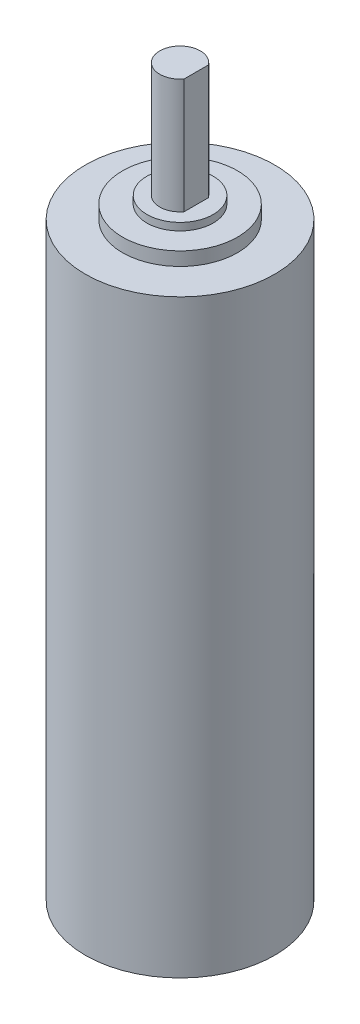
SolidWorks part; units mm, degrees
ref_plane "Спереди" through (0, 0, 0) normal (0, 0, 1) x (1, 0, 0)
ref_plane "Сверху" through (0, 0, 0) normal (0, 1, 0) x (1, 0, 0)
ref_plane "Справа" through (0, 0, 0) normal (1, 0, 0) x (0, 0, -1)
ref_plane "Плоскость1" through (0, 107.3, 0) normal (0, 1, 0) x (1, 0, 0)
ref_plane "Плоскость2" through (0, 90.3, 0) normal (0, 1, 0) x (1, 0, 0)
ref_plane "Плоскость3" through (0, 89.2, 0) normal (0, 1, 0) x (1, 0, 0)
ref_plane "Плоскость4" through (0, 87.2, 0) normal (0, 1, 0) x (1, 0, 0)
sketch "Эскиз1" plane through (0, 0, 0) normal (0, 1, 0) x (1, 0, 0)
  circle A0 centre (0, 0) radius 14
  dimension "D1" = 28
sketch "Эскиз2" plane through (0, 87.2, 0) normal (0, 1, 0) x (1, 0, 0)
  circle A0 centre (0, 0) radius 14 construction
  circle A1 centre (0, 0) radius 14
  circle A2 centre (0, 0) radius 8.5
  dimension "D1" = 17
sketch "Эскиз5" plane through (0, 89.2, 0) normal (0, 1, 0) x (1, 0, 0)
  circle A0 centre (0, 0) radius 8.5
  circle A1 centre (0, 0) radius 4.9
  dimension "D1" = 17
  dimension "D2" = 9.8
sketch "Эскиз8" plane through (0, 90.3, 0) normal (0, 1, 0) x (1, 0, 0)
  circle A0 centre (0, 0) radius 4.9
  circle A1 centre (0, 0) radius 3
  dimension "D1" = 9.8
  dimension "D2" = 6
sketch "Эскиз9" plane through (0, 107.3, 0) normal (0, 1, 0) x (1, 0, 0)
  circle A0 centre (0, 0) radius 3
  dimension "D1" = 6
loft "По сечениям2" add profiles "Эскиз1" section "Эскиз1" section "Эскиз2"
sketch "Эскиз10" plane through (0, 87.2, 0) normal (0, 1, 0) x (1, 0, 0)
  circle A0 centre (0, 0) radius 8.5 construction
  circle A1 centre (0, 0) radius 8.5
loft "По сечениям3" add profiles "Эскиз10" section "Эскиз10" section "Эскиз5"
sketch "Эскиз11" plane through (0, 89.2, 0) normal (0, 1, 0) x (1, 0, 0)
  circle A0 centre (0, 0) radius 4.9 construction
  circle A1 centre (0, 0) radius 4.9
loft "По сечениям4" add profiles "Эскиз11" section "Эскиз11" section "Эскиз8"
sketch "Эскиз12" plane through (0, 90.3, 0) normal (0, 1, 0) x (1, 0, 0)
  circle A0 centre (0, 0) radius 3 construction
  circle A1 centre (0, 0) radius 3
loft "По сечениям5" add profiles "Эскиз9", "Эскиз12"
sketch "Эскиз13" plane through (0, 107.3, 0) normal (0, 1, 0) x (1, 0, 0)
  line L0 (2.4, -1.8) -> (2.4, 1.8)
  circle A0 centre (0, 0) radius 3 construction
  circle A1 centre (0, 0) radius 3
  point P5 (1.3044, -2.7016)
  dimension "D1" = 2.4
extrude "Вырез-Вытянуть1" cut sketch "Эскиз13" against normal up to surface (17 mm away)
